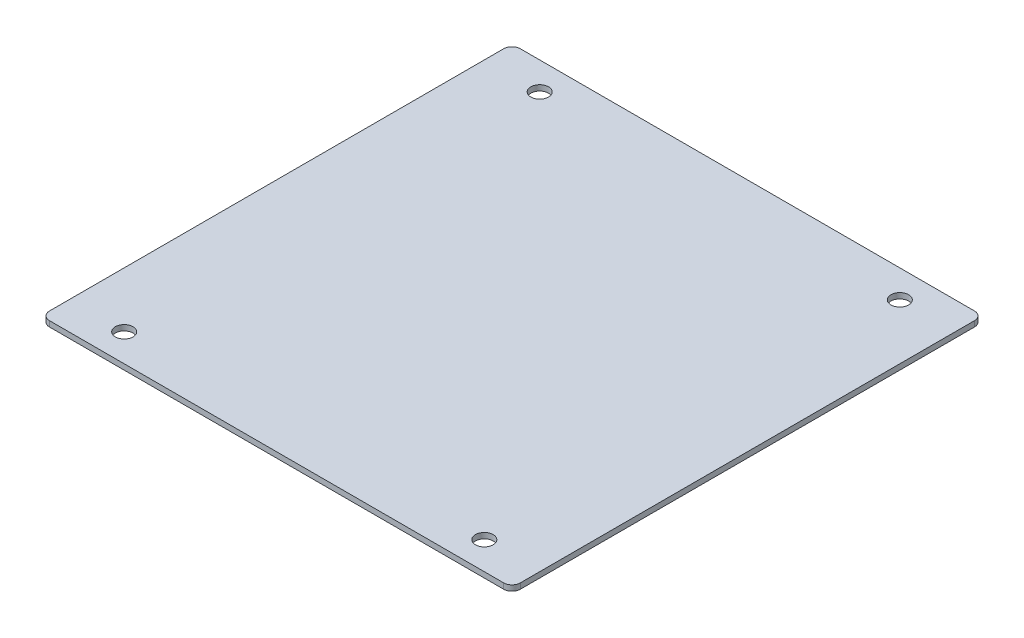
SolidWorks part; units mm, degrees
material "Plain Carbon Steel"
ref_plane "Front Plane" through (0, 0, 0) normal (0, 0, 1) x (1, 0, 0)
ref_plane "Top Plane" through (0, 0, 0) normal (0, 1, 0) x (1, 0, 0)
ref_plane "Right Plane" through (0, 0, 0) normal (1, 0, 0) x (0, 0, -1)
sketch "Sketch1" plane through (0, 0, 0) normal (0, 1, 0) x (1, 0, 0)
  line L1 (-85, -85) -> (85, -85)
  line L2 (-85, -85) -> (-85, 85)
  line L3 (-85, 85) -> (85, 85)
  line L4 (85, -85) -> (85, 85)
  line L5 (-85, -85) -> (85, 85) construction
  line L6 (-85, 85) -> (85, -85) construction
  point P0 (0, 0)
  dimension "D1" = 170
  dimension "D2" = 170
extrude "Boss-Extrude1" add sketch "Sketch1" along normal blind 2
fillet "Fillet1" radius 3 4 edges at (-85, 1, -85) (85, 1, -85) (85, 1, 85) (-85, 1, 85)
hole_wizard "M6 Clearance Hole1" positions "Sketch2" profile "Sketch3" hole size "M6" standard "ISO" end condition through all
sketch "Sketch2" plane through (0, 2, 0) normal (0, 1, 0) x (1, 0, 0)
  line L1 (-65, 75) -> (65, 75)
  line L2 (-65, 75) -> (-65, -75)
  line L3 (-65, -75) -> (65, -75)
  line L4 (65, 75) -> (65, -75)
  line L5 (0, 75) -> (0, 0) construction
  line L7 (0, 0) -> (-65, 0) construction
  point P1 (-65, 75)
  point P2 (65, -75)
  point P73 (-65, -75)
  point P74 (65, 75)
  dimension "D1" = 150
  dimension "D2" = 130
sketch "Sketch3" plane through (-65, 2, -75) normal (1, 0, 0) x (0, 0, 1)
  line L0 (0, 0) -> (0, 2)
  line L1 (0, 2) -> (3.2, 2)
  line L2 (3.2, 2) -> (3.2, 0)
  line L5 (3.2, 0) -> (0, 0)
  line L11 (0, -6.35) -> (0, 107.95) construction
  dimension "Thru Hole Dia." = 6.4
  dimension "Thru Hole Depth" = 2
